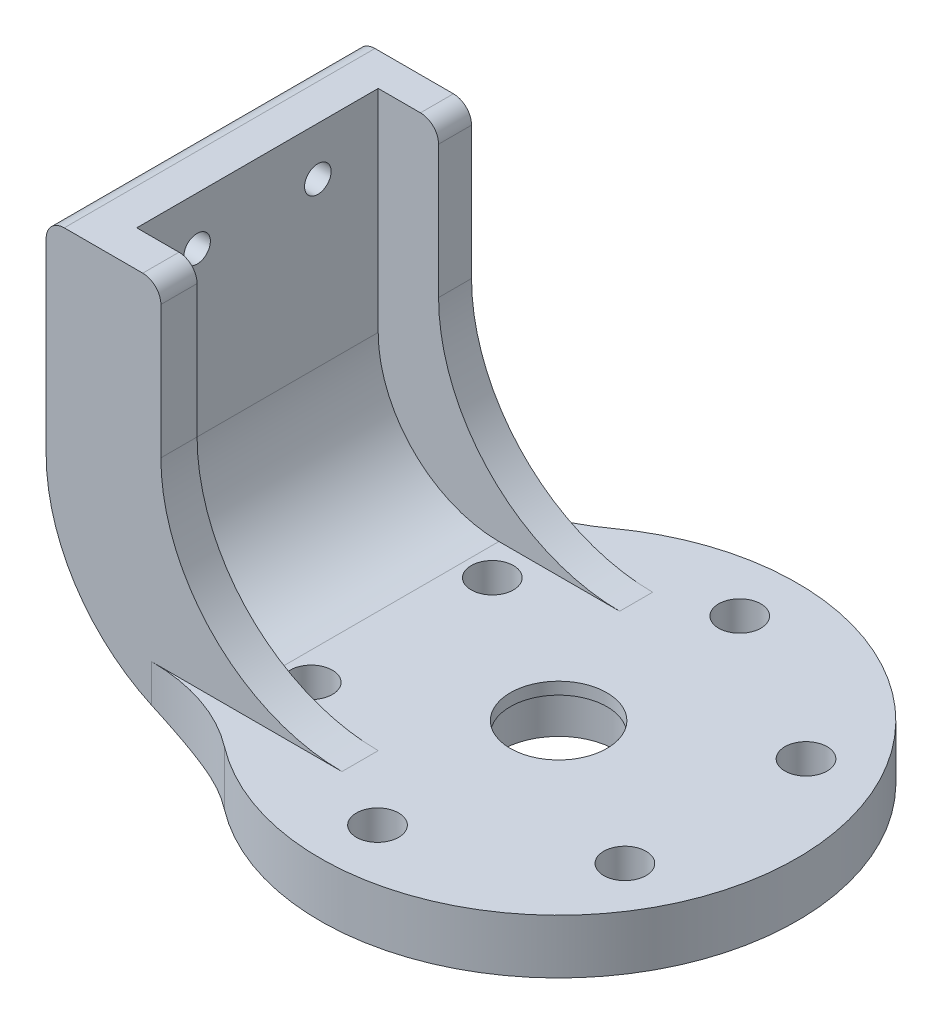
SolidWorks part; units mm, degrees
ref_plane "Front Plane" through (0, 0, 0) normal (0, 0, 1) x (1, 0, 0)
ref_plane "Top Plane" through (0, 0, 0) normal (0, 1, 0) x (1, 0, 0)
ref_plane "Right Plane" through (0, 0, 0) normal (1, 0, 0) x (0, 0, -1)
sketch "Sketch1" plane through (0, 0, 0) normal (0, 1, 0) x (1, 0, 0)
  line L0 (-13.6799, -98.3725) -> (-13.6799, -46.9101)
  line L1 (-13.6799, -46.9101) -> (5.0693, -46.9101)
  line L2 (3.5509, -46.9101) -> (5.0693, -46.9101)
  line L3 (-13.6799, -98.3725) -> (3.7953, -98.3725)
  arc A0 (21.9912, -104.5207) -> (22.7153, -41.1716) centre (45.9492, -73.1159) ccw
  circle A1 centre (45.9492, -73.1159) radius 9.52
  arc A2 (22.7153, -41.1716) -> (5.0693, -46.9101) centre (5.0693, -16.9101) cw
  arc A3 (21.9912, -104.5207) -> (3.7953, -98.3725) centre (3.7953, -128.3725) ccw
  dimension "D1" = 30
  dimension "D2" = 30
extrude "Boss-Extrude1" add sketch "Sketch1" along normal blind 9 contours A3 A0 A2 L1 L0 L3 A1
sketch "Sketch2" plane through (0, 9, 0) normal (0, 1, 0) x (1, 0, 0)
  line L1 (-13.6799, -46.9101) -> (-4.6799, -46.9101)
  line L2 (-13.6799, -46.9101) -> (-13.6799, -98.3725)
  line L3 (-13.6799, -98.3725) -> (-4.6799, -98.3725)
  line L4 (-4.6799, -52.3725) -> (-4.6799, -92.3725)
  line L5 (-4.6799, -46.9101) -> (5.3201, -46.9101)
  line L7 (-4.6799, -52.3725) -> (5.3201, -52.3725)
  line L8 (5.3201, -46.9101) -> (5.3201, -52.3725)
  line L9 (-4.6799, -98.3725) -> (5.3201, -98.3725)
  line L11 (-4.6799, -92.3725) -> (5.3201, -92.3725)
  line L12 (5.3201, -98.3725) -> (5.3201, -92.3725)
extrude "Boss-Extrude2" add sketch "Sketch2" along normal blind 55
fillet "Fillet1" radius 30 2 edges at (5.3201, 9, 95.3725) (5.3201, 9, 49.6413)
fillet "Fillet2" radius 20 1 edges at (-4.6799, 9, 72.3725)
fillet "Fillet3" radius 30 1 edges at (-13.6799, 0, 72.6413)
fillet "Fillet8" radius 3 3 edges at (5.3201, 64, 49.6413) (-13.6799, 64, 72.6413) (5.3201, 64, 95.3725)
sketch "Sketch3" plane through (-4.6799, 0, 0) normal (1, 0, 0) x (0, 0, -1)
  line L0 (-72.3725, 64) -> (-72.3725, 56)
  line L1 (-92.3725, 64) -> (-52.3725, 64) construction
  line L2 (-72.3725, 56) -> (-62.3725, 56)
  line L3 (-72.3725, 56) -> (-82.3725, 56)
  circle A0 centre (-62.3725, 56) radius 2.2
  circle A1 centre (-82.3725, 56) radius 2.2
extrude "Cut-Extrude1" cut sketch "Sketch3" against normal blind 56
sketch "Sketch4" plane through (0, 9, 0) normal (0, 1, 0) x (1, 0, 0)
  circle A0 centre (45.9492, -73.1159) radius 9.52
  circle A1 centre (45.9492, -73.1159) radius 8
extrude "Boss-Extrude3" add sketch "Sketch4" against normal blind 2
sketch "Sketch5" plane through (0, 0, 0) normal (0, -1, 0) x (1, 0, 0)
  circle A1 centre (19.9685, 88.1159) radius 3.5
  circle A2 centre (45.9492, 103.1159) radius 3.5
  circle A3 centre (71.93, 88.1159) radius 3.5
  circle A4 centre (71.93, 58.1159) radius 3.5
  circle A5 centre (45.9492, 43.1159) radius 3.5
  circle A6 centre (19.9685, 58.1159) radius 3.5
  point P17 (45.9492, 73.1159)
  dimension "D1" = 6
extrude "Cut-Extrude2" cut sketch "Sketch5" against normal blind 24
sketch "Sketch6" plane through (0, 0, 0) normal (0, -1, 0) x (1, 0, 0)
  circle A1 centre (35.9492, 90.4364) radius 3.5
  circle A2 centre (55.9492, 90.4364) radius 3.5
  circle A3 centre (65.9492, 73.1159) radius 3.5
  circle A4 centre (55.9492, 55.7953) radius 3.5
  circle A5 centre (35.9492, 55.7953) radius 3.5
  circle A6 centre (25.9492, 73.1159) radius 3.5
  point P17 (45.9492, 73.1159)
  dimension "D1" = 6
